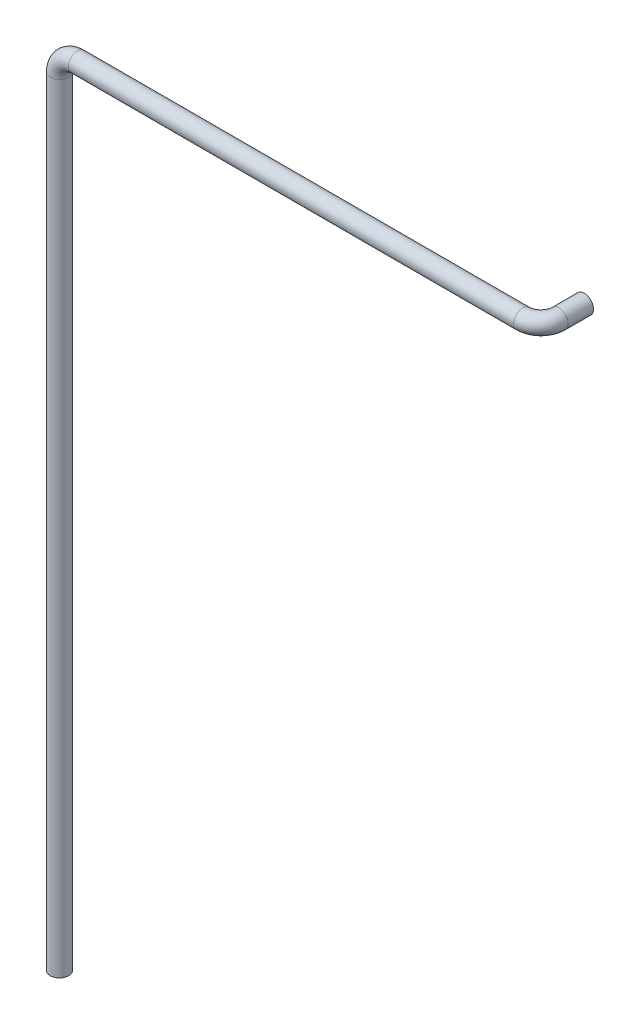
SolidWorks part; units mm, degrees
ref_plane "Alzado" through (0, 0, 0) normal (0, 0, 1) x (1, 0, 0)
ref_plane "Planta" through (0, 0, 0) normal (0, 1, 0) x (1, 0, 0)
ref_plane "Vista lateral" through (0, 0, 0) normal (1, 0, 0) x (0, 0, -1)
sketch "Croquis1" plane through (0, 0, 0) normal (0, 1, 0) x (1, 0, 0)
  circle A0 centre (0, 0) radius 12.7
  dimension "D1" = 25.4
extrude "Saliente-Extruir1" add sketch "Croquis1" along normal blind 860
sketch3d "Croquis3D1"
  line L0 (0, 860, 0) -> (0, 1075, 0)
  line L1 (0, 860, 0) -> (0, 0, 0) construction
  line L2 (25, 1100, 0) -> (640, 1100, 0)
  line L3 (665, 1100, -25) -> (665, 1100, -60)
  arc A0 (640, 1100, 0) -> (665, 1100, -25) centre (640, 1100, -25) ccw
  arc A1 (0, 1075, 0) -> (25, 1100, 0) centre (25, 1075, 0) ccw
  point P8 (665, 1100, 0)
  point P9 (640, 1125, -25)
  point P12 (0, 1100, 0)
  point P13 (25, 1075, -25)
  dimension "D4" = 25
  dimension "D1" = 240
  dimension "D2" = 665
  dimension "D3" = 60
sketch "Croquis2" plane through (0, 860, 0) normal (0, 1, 0) x (1, 0, 0)
  circle A0 centre (0, 0) radius 12.7
sweep "Barrer1" add profiles "Croquis2" path "Croquis3D1"
